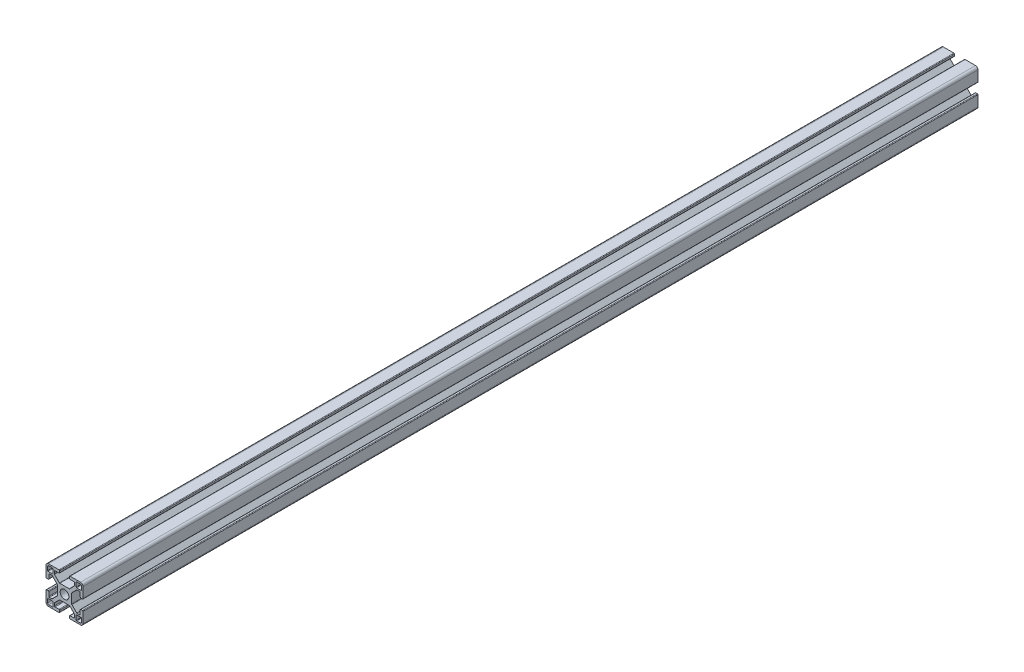
SolidWorks part; units mm, degrees
ref_plane "Front Plane" through (0, 0, 0) normal (0, 0, 1) x (1, 0, 0)
ref_plane "Top Plane" through (0, 0, 0) normal (0, 1, 0) x (1, 0, 0)
ref_plane "Right Plane" through (0, 0, 0) normal (1, 0, 0) x (0, 0, -1)
sketch "Sketch1" plane through (0, 0, 0) normal (0, 0, 1) x (1, 0, 0)
  line L0 (3.9799, -2.4733) -> (3.1981, -1.4942) construction
  line L1 (1.4942, -3.1981) -> (2.4733, -3.9799) construction
  line L2 (-2.4733, -3.9799) -> (-1.4942, -3.1981) construction
  line L3 (-3.1981, -1.4942) -> (-3.9799, -2.4733) construction
  line L4 (-3.9799, 2.4733) -> (-3.1981, 1.4942) construction
  line L5 (-1.4942, 3.1981) -> (-2.4733, 3.9799) construction
  line L6 (2.4733, 3.9799) -> (1.4942, 3.1981) construction
  line L7 (3.1981, 1.4942) -> (3.9799, 2.4733) construction
  line L8 (-12.6999, -13.6999) -> (-9.881, -13.6999)
  line L9 (-13.6999, -9.881) -> (-13.6999, -12.6999)
  line L10 (-9.88, -9.5) -> (-13.3189, -9.5)
  line L11 (-9.5, -13.3189) -> (-9.5, -9.88)
  line L12 (13.6999, -12.6999) -> (13.6999, -9.881)
  line L13 (9.881, -13.6999) -> (12.6999, -13.6999)
  line L14 (9.5, -9.88) -> (9.5, -13.3189)
  line L15 (13.3189, -9.5) -> (9.88, -9.5)
  line L16 (9.88, 9.5) -> (13.3189, 9.5)
  line L17 (9.5, 13.3189) -> (9.5, 9.88)
  line L18 (12.6999, 13.6999) -> (9.881, 13.6999)
  line L19 (13.6999, 9.881) -> (13.6999, 12.6999)
  line L20 (-13.6999, 12.6999) -> (-13.6999, 9.881)
  line L21 (-9.881, 13.6999) -> (-12.6999, 13.6999)
  line L22 (-9.5, 9.88) -> (-9.5, 13.3189)
  line L23 (-13.3189, 9.5) -> (-9.88, 9.5)
  line L24 (14.4999, -4) -> (13.2425, -4)
  line L25 (12.7425, -4.5) -> (12.7425, -7.7325)
  line L26 (12.2428, -8.25) -> (10.2602, -8.25)
  line L27 (9.9066, -8.1035) -> (5.9811, -4.178)
  line L28 (5.8347, -3.8245) -> (5.8347, -1.0125)
  line L29 (5.8347, -1.0125) -> (5.3247, -0.0625) construction
  line L30 (5.3247, -0.0625) -> (5.8347, 0.8875) construction
  line L31 (5.8347, 0.8875) -> (5.8347, 3.8245)
  line L32 (5.9811, 4.178) -> (9.9066, 8.1035)
  line L33 (10.2602, 8.25) -> (12.2428, 8.25)
  line L34 (12.7425, 7.7325) -> (12.7425, 4.5)
  line L35 (13.2425, 4) -> (14.4999, 4)
  line L36 (14.9999, 4.5) -> (14.9999, 12.9999)
  line L37 (12.9999, 14.9999) -> (4.5, 14.9999)
  line L38 (4, 14.4999) -> (4, 13.2425)
  line L39 (4.5, 12.7425) -> (7.7325, 12.7425)
  line L40 (8.25, 12.2428) -> (8.25, 10.2602)
  line L41 (8.1035, 9.9066) -> (4.178, 5.9811)
  line L42 (3.8245, 5.8347) -> (0.95, 5.8347)
  line L43 (0.95, 5.8347) -> (0, 5.3247) construction
  line L44 (0, 5.3247) -> (-0.95, 5.8347) construction
  line L45 (-0.95, 5.8347) -> (-3.8245, 5.8347)
  line L46 (-4.178, 5.9811) -> (-8.1035, 9.9066)
  line L47 (-8.25, 10.2602) -> (-8.25, 12.2428)
  line L48 (-7.7325, 12.7425) -> (-4.5, 12.7425)
  line L49 (-4, 13.2425) -> (-4, 14.4999)
  line L50 (-4.5, 14.9999) -> (-12.9999, 14.9999)
  line L51 (-14.9999, 12.9999) -> (-14.9999, 4.5)
  line L52 (-14.4999, 4) -> (-13.2425, 4)
  line L53 (-12.7425, 4.5) -> (-12.7425, 7.7325)
  line L54 (-12.2428, 8.25) -> (-10.2602, 8.25)
  line L55 (-9.9066, 8.1035) -> (-5.9811, 4.178)
  line L56 (-5.8347, 3.8245) -> (-5.8347, 0.8875)
  line L57 (-5.8347, 0.8875) -> (-5.3247, -0.0625) construction
  line L58 (-5.3247, -0.0625) -> (-5.8347, -1.0125) construction
  line L59 (-5.8347, -1.0125) -> (-5.8347, -3.8245)
  line L60 (-5.9811, -4.178) -> (-9.9066, -8.1035)
  line L61 (-10.2602, -8.25) -> (-12.2428, -8.25)
  line L62 (-12.7425, -7.7325) -> (-12.7425, -4.5)
  line L63 (-13.2425, -4) -> (-14.4999, -4)
  line L64 (-14.9999, -4.5) -> (-14.9999, -12.9999)
  line L65 (-12.9999, -14.9999) -> (-4.5, -14.9999)
  line L66 (-4, -14.4999) -> (-4, -13.2425)
  line L67 (-4.5, -12.7425) -> (-7.7325, -12.7425)
  line L68 (-8.25, -12.2428) -> (-8.25, -10.2602)
  line L69 (-8.1035, -9.9066) -> (-4.178, -5.9811)
  line L70 (-3.8245, -5.8347) -> (-0.95, -5.8347)
  line L71 (-0.95, -5.8347) -> (0, -5.3247) construction
  line L72 (0, -5.3247) -> (0.95, -5.8347) construction
  line L73 (0.95, -5.8347) -> (3.8245, -5.8347)
  line L74 (4.178, -5.9811) -> (8.1035, -9.9066)
  line L75 (8.25, -10.2602) -> (8.25, -12.2428)
  line L76 (7.7325, -12.7425) -> (4.5, -12.7425)
  line L77 (4, -13.2425) -> (4, -14.4999)
  line L78 (4.5, -14.9999) -> (12.9999, -14.9999)
  line L79 (14.9999, -12.9999) -> (14.9999, -4.5)
  line L80 (-5.8347, -1.0125) -> (-5.8347, 0.8875)
  line L81 (-0.95, 5.8347) -> (0.95, 5.8347)
  line L82 (5.8347, 0.8875) -> (5.8347, -1.0125)
  line L83 (-0.95, -5.8347) -> (0.95, -5.8347)
  arc A0 (2.4733, -3.9799) -> (3.9799, -2.4733) centre (3.1422, -3.1422) ccw construction
  arc A1 (-1.4942, -3.1981) -> (1.4942, -3.1981) centre (0, 0) ccw construction
  arc A2 (-3.9799, -2.4733) -> (-2.4733, -3.9799) centre (-3.1422, -3.1422) ccw construction
  arc A3 (-3.1981, 1.4942) -> (-3.1981, -1.4942) centre (0, 0) ccw construction
  arc A4 (-2.4733, 3.9799) -> (-3.9799, 2.4733) centre (-3.1422, 3.1422) ccw construction
  arc A5 (1.4942, 3.1981) -> (-1.4942, 3.1981) centre (0, 0) ccw construction
  arc A6 (3.9799, 2.4733) -> (2.4733, 3.9799) centre (3.1422, 3.1422) ccw construction
  arc A7 (3.1981, -1.4942) -> (3.1981, 1.4942) centre (0, 0) ccw construction
  arc A8 (-13.6999, -12.6999) -> (-12.6999, -13.6999) centre (-12.6999, -12.6999) ccw
  arc A9 (-13.3189, -9.5) -> (-13.6999, -9.881) centre (-13.3189, -9.881) ccw
  arc A10 (-9.5, -9.88) -> (-9.88, -9.5) centre (-9.88, -9.88) ccw
  arc A11 (-9.881, -13.6999) -> (-9.5, -13.3189) centre (-9.881, -13.3189) ccw
  arc A12 (12.6999, -13.6999) -> (13.6999, -12.6999) centre (12.6999, -12.6999) ccw
  arc A13 (9.5, -13.3189) -> (9.881, -13.6999) centre (9.881, -13.3189) ccw
  arc A14 (9.88, -9.5) -> (9.5, -9.88) centre (9.88, -9.88) ccw
  arc A15 (13.6999, -9.881) -> (13.3189, -9.5) centre (13.3189, -9.881) ccw
  arc A16 (9.5, 9.88) -> (9.88, 9.5) centre (9.88, 9.88) ccw
  arc A17 (9.881, 13.6999) -> (9.5, 13.3189) centre (9.881, 13.3189) ccw
  arc A18 (13.6999, 12.6999) -> (12.6999, 13.6999) centre (12.6999, 12.6999) ccw
  arc A19 (13.3189, 9.5) -> (13.6999, 9.881) centre (13.3189, 9.881) ccw
  arc A20 (14.9999, -4.5) -> (14.4999, -4) centre (14.4999, -4.5) ccw
  arc A21 (13.2425, -4) -> (12.7425, -4.5) centre (13.2425, -4.5) ccw
  arc A22 (12.2428, -8.25) -> (12.7425, -7.7325) centre (12.2428, -7.75) ccw
  arc A23 (9.9066, -8.1035) -> (10.2602, -8.25) centre (10.2602, -7.75) ccw
  arc A24 (5.8347, -3.8245) -> (5.9811, -4.178) centre (6.3347, -3.8245) ccw
  arc A25 (5.9811, 4.178) -> (5.8347, 3.8245) centre (6.3347, 3.8245) ccw
  arc A26 (10.2602, 8.25) -> (9.9066, 8.1035) centre (10.2602, 7.75) ccw
  arc A27 (12.7425, 7.7325) -> (12.2428, 8.25) centre (12.2428, 7.75) ccw
  arc A28 (12.7425, 4.5) -> (13.2425, 4) centre (13.2425, 4.5) ccw
  arc A29 (14.4999, 4) -> (14.9999, 4.5) centre (14.4999, 4.5) ccw
  arc A30 (14.9999, 12.9999) -> (12.9999, 14.9999) centre (12.9999, 12.9999) ccw
  arc A31 (4.5, 14.9999) -> (4, 14.4999) centre (4.5, 14.4999) ccw
  arc A32 (4, 13.2425) -> (4.5, 12.7425) centre (4.5, 13.2425) ccw
  arc A33 (8.25, 12.2428) -> (7.7325, 12.7425) centre (7.75, 12.2428) ccw
  arc A34 (8.1035, 9.9066) -> (8.25, 10.2602) centre (7.75, 10.2602) ccw
  arc A35 (3.8245, 5.8347) -> (4.178, 5.9811) centre (3.8245, 6.3347) ccw
  arc A36 (-4.178, 5.9811) -> (-3.8245, 5.8347) centre (-3.8245, 6.3347) ccw
  arc A37 (-8.25, 10.2602) -> (-8.1035, 9.9066) centre (-7.75, 10.2602) ccw
  arc A38 (-7.7325, 12.7425) -> (-8.25, 12.2428) centre (-7.75, 12.2428) ccw
  arc A39 (-4.5, 12.7425) -> (-4, 13.2425) centre (-4.5, 13.2425) ccw
  arc A40 (-4, 14.4999) -> (-4.5, 14.9999) centre (-4.5, 14.4999) ccw
  arc A41 (-12.9999, 14.9999) -> (-14.9999, 12.9999) centre (-12.9999, 12.9999) ccw
  arc A42 (-14.9999, 4.5) -> (-14.4999, 4) centre (-14.4999, 4.5) ccw
  arc A43 (-13.2425, 4) -> (-12.7425, 4.5) centre (-13.2425, 4.5) ccw
  arc A44 (-12.2428, 8.25) -> (-12.7425, 7.7325) centre (-12.2428, 7.75) ccw
  arc A45 (-9.9066, 8.1035) -> (-10.2602, 8.25) centre (-10.2602, 7.75) ccw
  arc A46 (-5.8347, 3.8245) -> (-5.9811, 4.178) centre (-6.3347, 3.8245) ccw
  arc A47 (-5.9811, -4.178) -> (-5.8347, -3.8245) centre (-6.3347, -3.8245) ccw
  arc A48 (-10.2602, -8.25) -> (-9.9066, -8.1035) centre (-10.2602, -7.75) ccw
  arc A49 (-12.7425, -7.7325) -> (-12.2428, -8.25) centre (-12.2428, -7.75) ccw
  arc A50 (-12.7425, -4.5) -> (-13.2425, -4) centre (-13.2425, -4.5) ccw
  arc A51 (-14.4999, -4) -> (-14.9999, -4.5) centre (-14.4999, -4.5) ccw
  arc A52 (-14.9999, -12.9999) -> (-12.9999, -14.9999) centre (-12.9999, -12.9999) ccw
  arc A53 (-4.5, -14.9999) -> (-4, -14.4999) centre (-4.5, -14.4999) ccw
  arc A54 (-4, -13.2425) -> (-4.5, -12.7425) centre (-4.5, -13.2425) ccw
  arc A55 (-8.25, -12.2428) -> (-7.7325, -12.7425) centre (-7.75, -12.2428) ccw
  arc A56 (-8.1035, -9.9066) -> (-8.25, -10.2602) centre (-7.75, -10.2602) ccw
  arc A57 (-3.8245, -5.8347) -> (-4.178, -5.9811) centre (-3.8245, -6.3347) ccw
  arc A58 (4.178, -5.9811) -> (3.8245, -5.8347) centre (3.8245, -6.3347) ccw
  arc A59 (8.25, -10.2602) -> (8.1035, -9.9066) centre (7.75, -10.2602) ccw
  arc A60 (7.7325, -12.7425) -> (8.25, -12.2428) centre (7.75, -12.2428) ccw
  arc A61 (4.5, -12.7425) -> (4, -13.2425) centre (4.5, -13.2425) ccw
  arc A62 (4, -14.4999) -> (4.5, -14.9999) centre (4.5, -14.4999) ccw
  arc A63 (12.9999, -14.9999) -> (14.9999, -12.9999) centre (12.9999, -12.9999) ccw
  arc A64 (-12.6999, 13.6999) -> (-13.6999, 12.6999) centre (-12.6999, 12.6999) ccw
  arc A65 (-9.5, 13.3189) -> (-9.881, 13.6999) centre (-9.881, 13.3189) ccw
  arc A66 (-9.88, 9.5) -> (-9.5, 9.88) centre (-9.88, 9.88) ccw
  arc A67 (-13.6999, 9.881) -> (-13.3189, 9.5) centre (-13.3189, 9.881) ccw
  circle A68 centre (0, 0) radius 3.53
extrude "Boss-Extrude1" add sketch "Sketch1" along normal mid plane 725.4875
